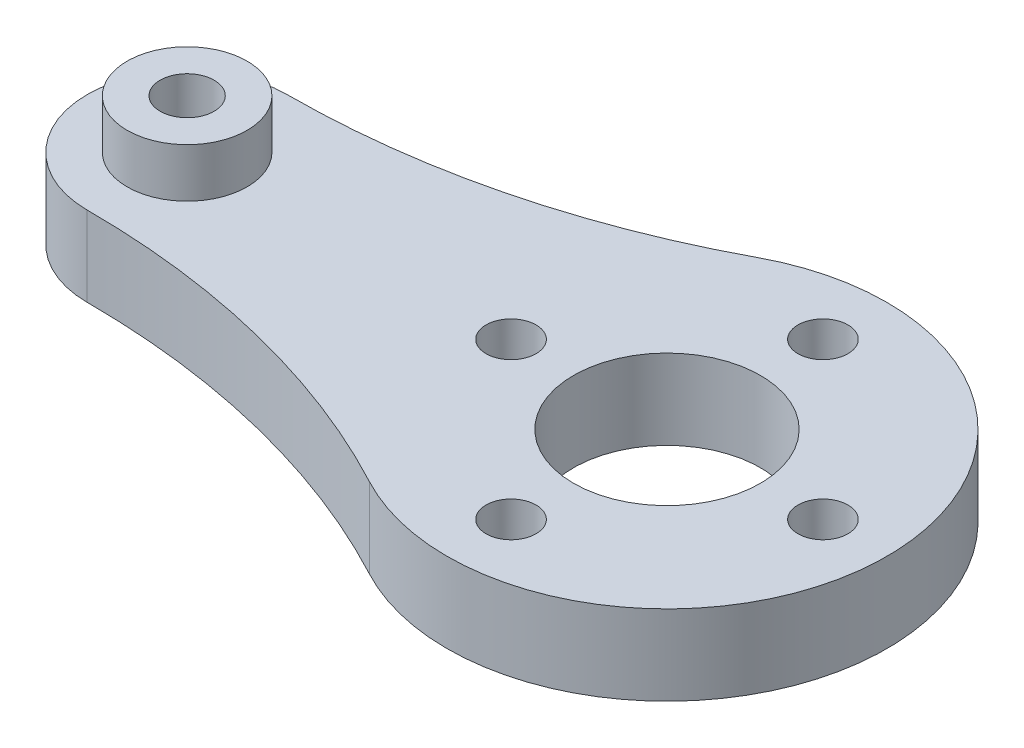
SolidWorks part; units mm, degrees
ref_plane "Front Plane" through (0, 0, 0) normal (0, 0, 1) x (1, 0, 0)
ref_plane "Top Plane" through (0, 0, 0) normal (0, 1, 0) x (1, 0, 0)
ref_plane "Right Plane" through (0, 0, 0) normal (1, 0, 0) x (0, 0, -1)
sketch "Sketch1" plane through (0, 0, 0) normal (0, 1, 0) x (1, 0, 0)
  line L0 (-12, 0) -> (12, 0) construction
  line L1 (-14.7145, -5) -> (-9.2855, -5) construction
  circle A0 centre (12, 0) radius 4.375 construction
  circle A1 centre (12, 0) radius 7.8 construction
  circle A2 centre (4.2, 0) radius 1.25
  circle A4 centre (-12, 0) radius 1.35
  circle A7 centre (12, 7.8) radius 1.25
  circle A8 centre (19.8, 0) radius 1.25
  circle A9 centre (12, -7.8) radius 1.25
  arc A10 (6.8235, -9.7059) -> (6.8235, 9.7059) centre (12, 0) ccw
  arc A11 (-12, 5) -> (-12, -5) centre (-12, 0) ccw
  arc A13 (6.8235, -9.7059) -> (-12, -5) centre (-12, -45) ccw
  arc A14 (6.8235, 9.7059) -> (-12, 5) centre (-12, 45) cw
  circle A15 centre (12, 0) radius 4.675
  point P4 (0, 0)
  point P16 (-12, -5)
  point P23 (12, 0)
  point P29 (-12, -5)
  dimension "D2" = 8.75
  dimension "D3" = 15.6
  dimension "D4" = 2.5
  dimension "D5" = 2.7
  dimension "D6" = 22
  dimension "D7" = 10
  dimension "D9" = 0.3
  dimension "D1" = 24
  dimension "D8" = 4
extrude "Boss-Extrude2" add sketch "Sketch1" along normal blind 4
sketch "Sketch2" plane through (0, 0, 0) normal (0, -1, 0) x (1, 0, 0)
  circle A0 centre (12, -7.8) radius 2.75
  circle A1 centre (4.2, 0) radius 2.75
  circle A2 centre (12, 7.8) radius 2.75
  circle A3 centre (19.8, 0) radius 2.75
  point P3 (12, 0)
  point P14 (12, 0)
  dimension "D1" = 5.5
  dimension "D2" = 4
extrude "Cut-Extrude1" cut sketch "Sketch2" against normal blind 1
sketch "Sketch4" plane through (0, 4, 0) normal (0, 1, 0) x (1, 0, 0)
  circle A0 centre (-12, 0) radius 3
  circle A1 centre (-12, 0) radius 1.35 construction
  circle A2 centre (-12, 0) radius 1.35
  dimension "D1" = 6
extrude "Boss-Extrude3" add sketch "Sketch4" along normal blind 2.45
